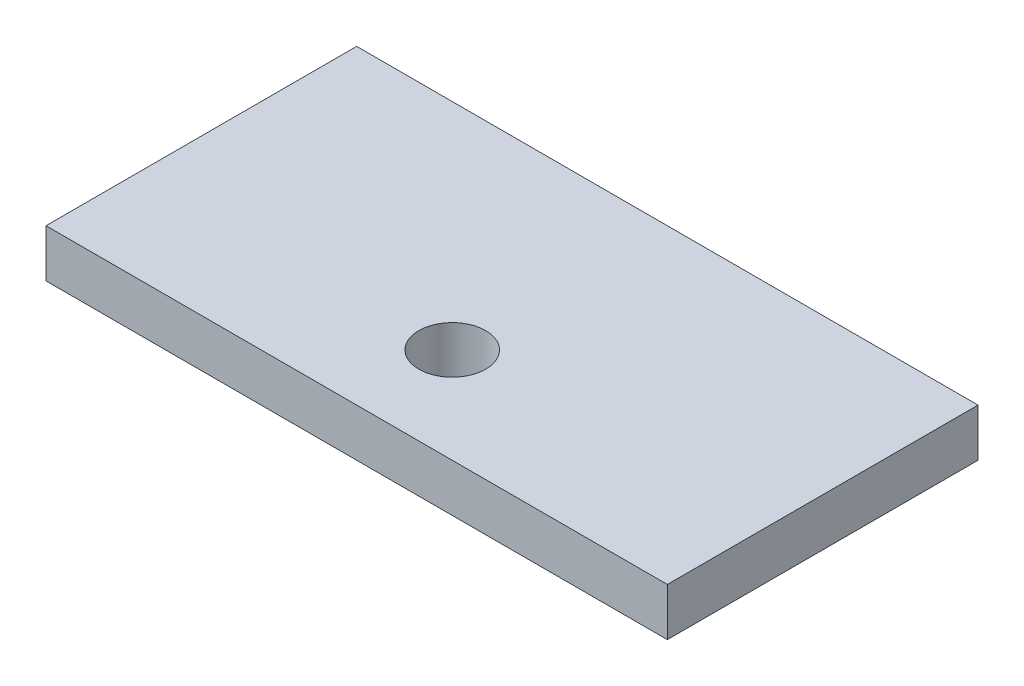
SolidWorks part; units mm, degrees
material "6061 Alloy"
ref_plane "Front Plane" through (0, 0, 0) normal (0, 0, 1) x (1, 0, 0)
ref_plane "Top Plane" through (0, 0, 0) normal (0, 1, 0) x (1, 0, 0)
ref_plane "Right Plane" through (0, 0, 0) normal (1, 0, 0) x (0, 0, -1)
sketch "Sketch1" plane through (0, 0, 0) normal (0, 1, 0) x (1, 0, 0)
  line L1 (-65, -32.5) -> (65, -32.5)
  line L2 (-65, -32.5) -> (-65, 32.5)
  line L3 (-65, 32.5) -> (65, 32.5)
  line L4 (65, -32.5) -> (65, 32.5)
  line L5 (-65, -32.5) -> (65, 32.5) construction
  line L6 (-65, 32.5) -> (65, -32.5) construction
  point P0 (0, 0)
  dimension "D1" = 130
  dimension "D2" = 65
extrude "Boss-Extrude1" add sketch "Sketch1" along normal blind 10
sketch "Sketch2" plane through (0, 0, 0) normal (0, 1, 0) x (1, 0, 0)
  line L0 (0, -12.5) -> (0, 781.074) construction
  line L1 (-65, -32.5) -> (65, -32.5) construction
  line L2 (0, -12.5) -> (979.3965, -12.5) construction
  circle A0 centre (0, -12.5) radius 7
  dimension "D1" = 14
  dimension "D2" = 20
extrude "Cut-Extrude2" cut sketch "Sketch2" against normal through all and the other way through all
